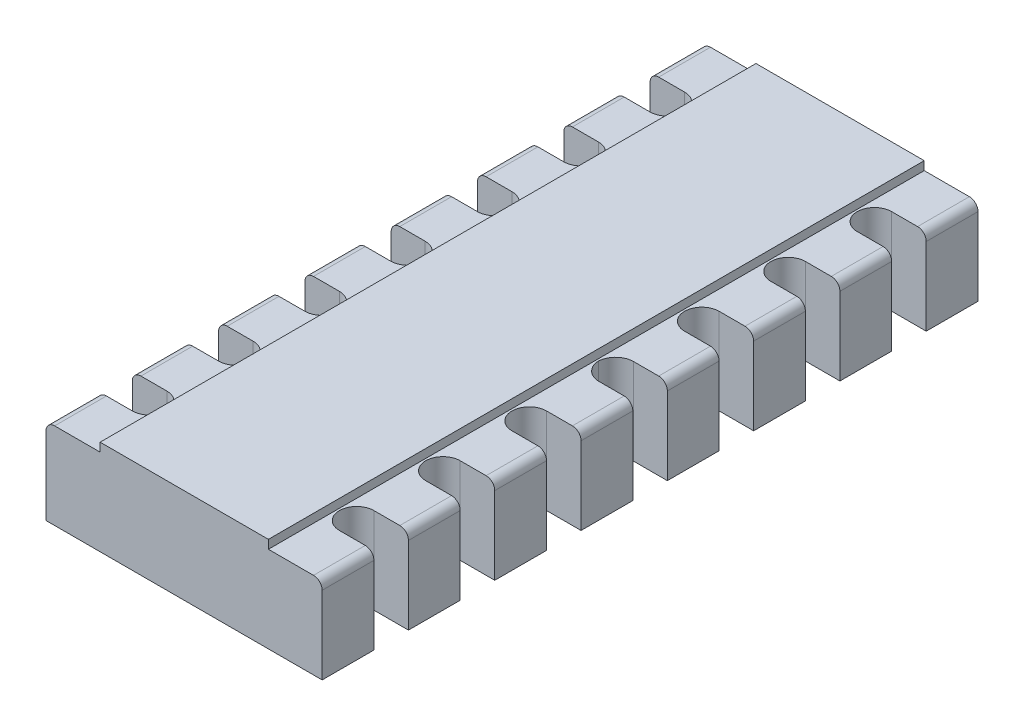
SolidWorks part; units mm, degrees
ref_plane "Front Plane" through (0, 0, 0) normal (0, 0, 1) x (1, 0, 0)
ref_plane "Top Plane" through (0, 0, 0) normal (0, 1, 0) x (1, 0, 0)
ref_plane "Right Plane" through (0, 0, 0) normal (1, 0, 0) x (0, 0, -1)
sketch "Sketch1" plane through (0, 0, 0) normal (0, 1, 0) x (1, 0, 0)
  line L0 (0, 2.3267) -> (0, -2.2841) construction
  line L1 (-2.4335, 0) -> (1.9212, 0) construction
  line L3 (-0.8, 1.9) -> (-0.8, 1.6)
  line L4 (-0.8, 1.6) -> (-0.6, 1.6)
  line L5 (-0.6, 1.4) -> (-0.8, 1.4)
  line L6 (-0.8, 1.4) -> (-0.8, 1.1)
  line L7 (-0.8, 1.1) -> (-0.6, 1.1)
  line L8 (-0.6, 0.9) -> (-0.8, 0.9)
  line L30 (-0.8, 0.9) -> (-0.8, 0.6)
  line L31 (-0.8, 0.6) -> (-0.6, 0.6)
  line L32 (-0.6, 0.4) -> (-0.8, 0.4)
  line L33 (-0.8, 0.4) -> (-0.8, 0.1)
  line L34 (-0.8, 1.6) -> (-0.8, 1.3862) construction
  line L35 (-0.8, 0.1) -> (-0.6046, 0.1)
  line L36 (-0.8, 1.9) -> (0.8, 1.9)
  line L37 (0.8, 1.6) -> (0.8, 1.3862) construction
  line L38 (0.8, 0.1) -> (0.6046, 0.1)
  line L39 (0.8, 0.4) -> (0.8, 0.1)
  line L40 (0.6, 0.4) -> (0.8, 0.4)
  line L41 (0.8, 0.6) -> (0.6, 0.6)
  line L42 (0.8, 0.9) -> (0.8, 0.6)
  line L43 (0.6, 0.9) -> (0.8, 0.9)
  line L44 (0.8, 1.1) -> (0.6, 1.1)
  line L45 (0.8, 1.4) -> (0.8, 1.1)
  line L46 (0.6, 1.4) -> (0.8, 1.4)
  line L47 (0.8, 1.6) -> (0.6, 1.6)
  line L48 (0.8, 1.9) -> (0.8, 1.6)
  line L49 (0.8, -1.6) -> (0.8, -1.3862) construction
  line L50 (-0.8, -1.6) -> (-0.8, -1.3862) construction
  line L51 (0.8, -1.9) -> (0.8, -1.6)
  line L52 (0.8, -1.6) -> (0.6, -1.6)
  line L53 (0.6, -1.4) -> (0.8, -1.4)
  line L54 (0.8, -1.4) -> (0.8, -1.1)
  line L55 (0.8, -1.1) -> (0.6, -1.1)
  line L56 (0.6, -0.9) -> (0.8, -0.9)
  line L57 (0.8, -0.9) -> (0.8, -0.6)
  line L58 (0.8, -0.6) -> (0.6, -0.6)
  line L59 (0.6, -0.4) -> (0.8, -0.4)
  line L60 (0.8, -0.4) -> (0.8, -0.1)
  line L61 (0.8, -0.1) -> (0.6046, -0.1)
  line L62 (-0.8, -1.9) -> (0.8, -1.9)
  line L63 (-0.8, -0.1) -> (-0.6046, -0.1)
  line L64 (-0.8, -0.4) -> (-0.8, -0.1)
  line L65 (-0.6, -0.4) -> (-0.8, -0.4)
  line L66 (-0.8, -0.6) -> (-0.6, -0.6)
  line L67 (-0.8, -0.9) -> (-0.8, -0.6)
  line L68 (-0.6, -0.9) -> (-0.8, -0.9)
  line L69 (-0.8, -1.1) -> (-0.6, -1.1)
  line L70 (-0.8, -1.4) -> (-0.8, -1.1)
  line L71 (-0.6, -1.4) -> (-0.8, -1.4)
  line L72 (-0.8, -1.6) -> (-0.6, -1.6)
  line L73 (-0.8, -1.9) -> (-0.8, -1.6)
  arc A0 (-0.6, 1.6) -> (-0.6, 1.4) centre (-0.6, 1.5) cw
  arc A1 (-0.6, 1.1) -> (-0.6, 0.9) centre (-0.6, 1) cw
  arc A8 (-0.6, 0.6) -> (-0.6, 0.4) centre (-0.6, 0.5) cw
  arc A9 (-0.6046, 0.1) -> (-0.5, 0) centre (-0.6046, -0.0047) cw
  arc A10 (0.6046, 0.1) -> (0.5, 0) centre (0.6046, -0.0047) ccw
  arc A11 (0.6, 0.6) -> (0.6, 0.4) centre (0.6, 0.5) ccw
  arc A12 (0.6, 1.1) -> (0.6, 0.9) centre (0.6, 1) ccw
  arc A13 (0.6, 1.6) -> (0.6, 1.4) centre (0.6, 1.5) ccw
  arc A14 (0.6, -1.6) -> (0.6, -1.4) centre (0.6, -1.5) cw
  arc A15 (0.6, -1.1) -> (0.6, -0.9) centre (0.6, -1) cw
  arc A16 (0.6, -0.6) -> (0.6, -0.4) centre (0.6, -0.5) cw
  arc A17 (0.6046, -0.1) -> (0.5, 0) centre (0.6046, 0.0047) cw
  arc A18 (-0.6046, -0.1) -> (-0.5, 0) centre (-0.6046, 0.0047) ccw
  arc A19 (-0.6, -0.6) -> (-0.6, -0.4) centre (-0.6, -0.5) ccw
  arc A20 (-0.6, -1.1) -> (-0.6, -0.9) centre (-0.6, -1) ccw
  arc A21 (-0.6, -1.6) -> (-0.6, -1.4) centre (-0.6, -1.5) ccw
  point P31 (0, 1.9)
  point P34 (0, 1.9)
  point P48 (0.8, 0)
  point P49 (-0.8, 0)
  point P59 (-0.8, 1.75)
  point P60 (-0.8, 1.25)
  point P61 (-0.5, 1.5)
  point P67 (-0.5, 0.5)
  point P95 (0, -1.9)
  dimension "D4" = 0.3
  dimension "D1" = 0.3
  dimension "D2" = 0.8
  dimension "D5" = 0.5
  dimension "D6" = 0.3
extrude "Boss-Extrude1" add sketch "Sketch1" along normal blind 0.5
sketch "Sketch2" plane through (0, 0.5, 0) normal (0, 1, 0) x (1, 0, 0)
  line L0 (-0.8, -1.9) -> (0.8, -1.9) construction
  line L1 (-0.4864, -1.9) -> (0.4886, -1.9)
  line L2 (-0.4864, -1.9) -> (-0.4864, 1.9)
  line L3 (-0.4864, 1.9) -> (0.4886, 1.9)
  line L4 (0.4886, -1.9) -> (0.4886, 1.9)
  line L5 (0.8, 1.9) -> (-0.8, 1.9) construction
extrude "Boss-Extrude2" add sketch "Sketch2" along normal blind 0.05
fillet "Fillet2" radius 0.05 16 edges at (0.8, 0.5, 1.25) (0.8, 0.5, 0.75) (0.8, 0.5, 0.25) (0.8, 0.5, -0.75) (0.8, 0.5, -0.25) (0.8, 0.5, -1.25) (0.8, 0.5, -1.75) (-0.8, 0.5, -0.75) (-0.8, 0.5, -1.25) (-0.8, 0.5, -1.75) (-0.8, 0.5, -0.25) (-0.8, 0.5, 0.25) (0.8, 0.5, 1.75) (-0.8, 0.5, 0.75) (-0.8, 0.5, 1.25) (-0.8, 0.5, 1.75)
